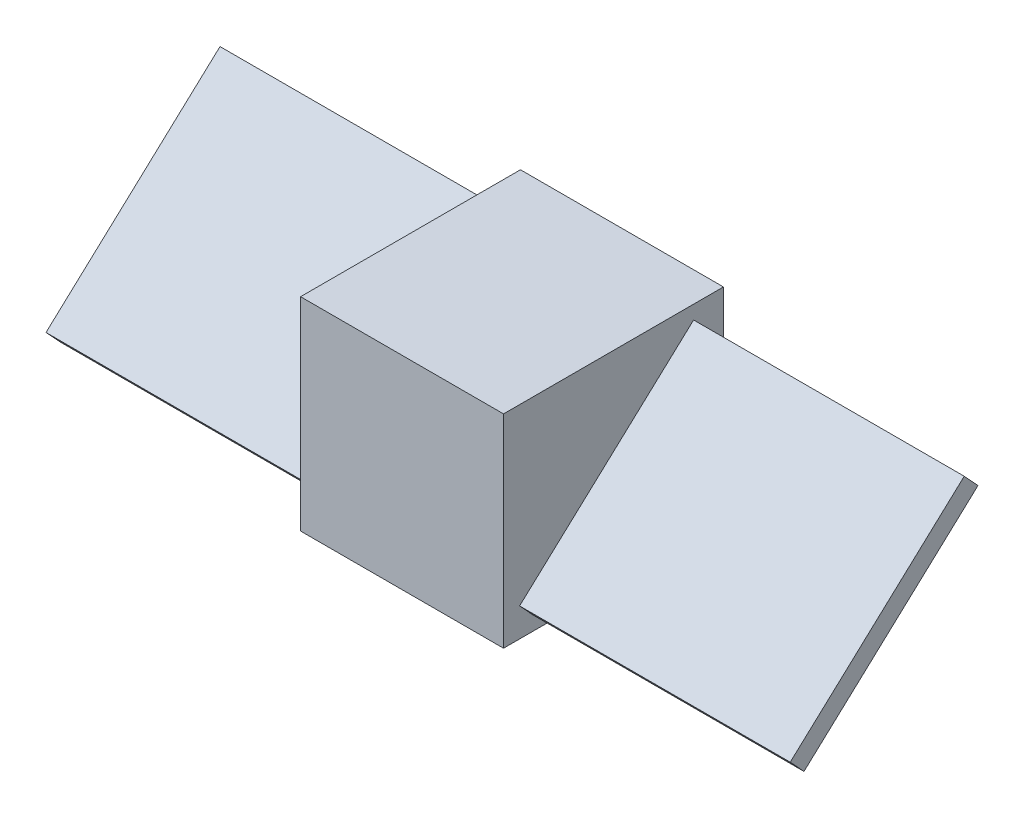
SolidWorks part; units mm, degrees
ref_plane "Front Plane" through (0, 0, 0) normal (0, 0, 1) x (1, 0, 0)
ref_plane "Top Plane" through (0, 0, 0) normal (0, 1, 0) x (1, 0, 0)
ref_plane "Right Plane" through (0, 0, 0) normal (1, 0, 0) x (0, 0, -1)
sketch "Sketch1" plane through (0, 0, 0) normal (0, 1, 0) x (1, 0, 0)
  line L1 (-30, -32.5) -> (30, -32.5)
  line L2 (-30, -32.5) -> (-30, 32.5)
  line L3 (-30, 32.5) -> (30, 32.5)
  line L4 (30, -32.5) -> (30, 32.5)
  line L5 (-30, -32.5) -> (30, 32.5) construction
  line L6 (-30, 32.5) -> (30, -32.5) construction
  point P0 (0, 0)
  dimension "D1" = 60
  dimension "D2" = 65
extrude "Boss-Extrude1" add sketch "Sketch1" along normal blind 60
sketch "Sketch2" plane through (30, 0, 0) normal (1, 0, 0) x (0, 0, -1)
  line L0 (-32.5, 0) -> (32.5, 60) construction
  line L1 (-30.4652, -2.2044) -> (34.5348, 57.7956)
  line L2 (-34.5348, 2.2044) -> (30.4652, 62.2044)
  line L3 (-27.753, 8.4646) -> (-23.6833, 4.0558)
  line L4 (-32.5, 0) -> (32.5, 0)
  line L5 (32.5, 0) -> (32.5, 60)
  line L6 (32.5, 60) -> (-32.5, 60)
  line L7 (-32.5, 60) -> (-32.5, 0)
  line L8 (-32.5, 0) -> (32.5, 0) construction
  line L9 (32.5, 0) -> (32.5, 60) construction
  line L10 (32.5, 60) -> (-32.5, 60) construction
  line L11 (-32.5, 60) -> (-32.5, 0) construction
  line L12 (-2.0348, 32.2044) -> (2.0348, 27.7956) construction
  line L13 (23.6833, 55.9442) -> (27.753, 51.5354)
  dimension "D3" = 35
  dimension "D1" = 0
  dimension "D2" = 3
extrude "Boss-Extrude2" add sketch "Sketch2" along normal blind 80 separate body contours L13 L2 L3 L1
ref_plane "Plane1" through (0, 0, 0) normal (1, 0, 0) x (0, 0, -1)
mirror "Mirror1" about plane through (0, 0, 0) normal (1, 0, 0) of bodies 102
equation "\"WingSpanDim\"= 80"
equation "\"D1@Boss-Extrude2\"=\"WingSpanDim\""
equation "\"WingWidth\" = 3"
equation "\"WingSize\"= 35"
equation "\"D3@Sketch2\"=\"WingSize\""
equation "\"D2@Sketch2\"=\"WingWidth\""
